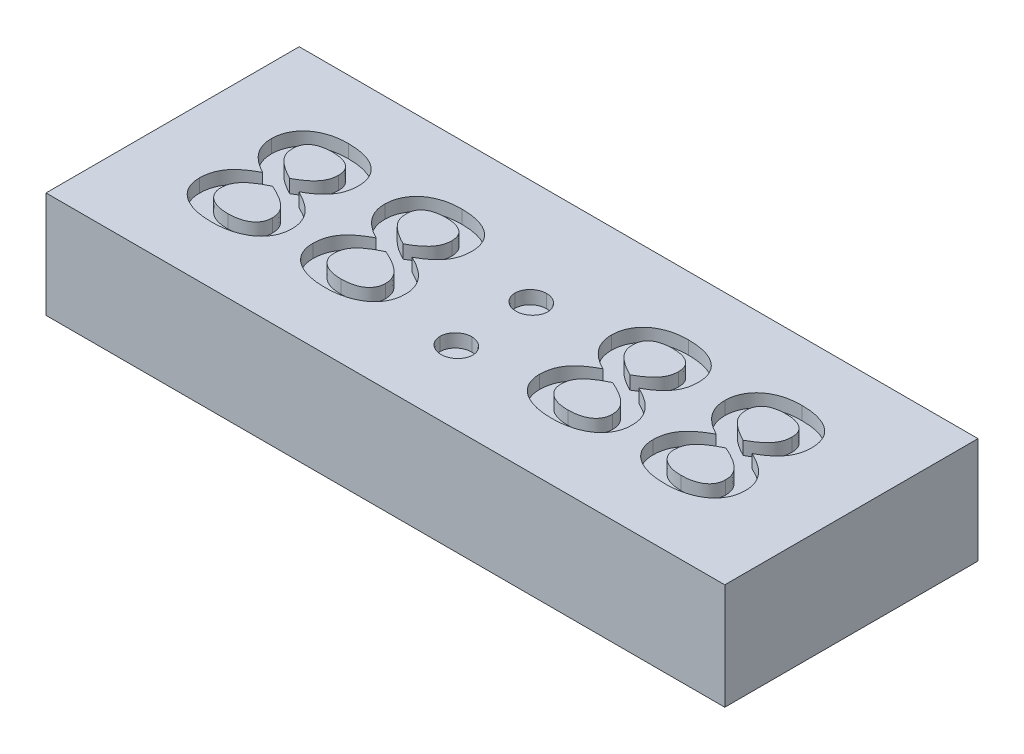
SolidWorks part; units mm, degrees
material "ABS White"
ref_plane "Front Plane" through (0, 0, 0) normal (0, 0, 1) x (1, 0, 0)
ref_plane "Top Plane" through (0, 0, 0) normal (0, 1, 0) x (1, 0, 0)
ref_plane "Right Plane" through (0, 0, 0) normal (1, 0, 0) x (0, 0, -1)
sketch "Sketch1" plane through (0, 0, 0) normal (0, 1, 0) x (1, 0, 0)
  line L1 (0, 0) -> (51.2, 0)
  line L2 (0, 0) -> (0, 19.1)
  line L3 (0, 19.1) -> (51.2, 19.1)
  line L4 (51.2, 0) -> (51.2, 19.1)
  dimension "D1" = 51.2
  dimension "D2" = 19.1
extrude "Boss-Extrude1" add sketch "Sketch1" along normal blind 8
sketch "Sketch2" plane through (0, 8, 0) normal (0, 1, 0) x (1, 0, 0)
  text T0 "88:88" font "Consolas" height 10
extrude "Cut-Extrude1" cut sketch "Sketch2" against normal blind 1
